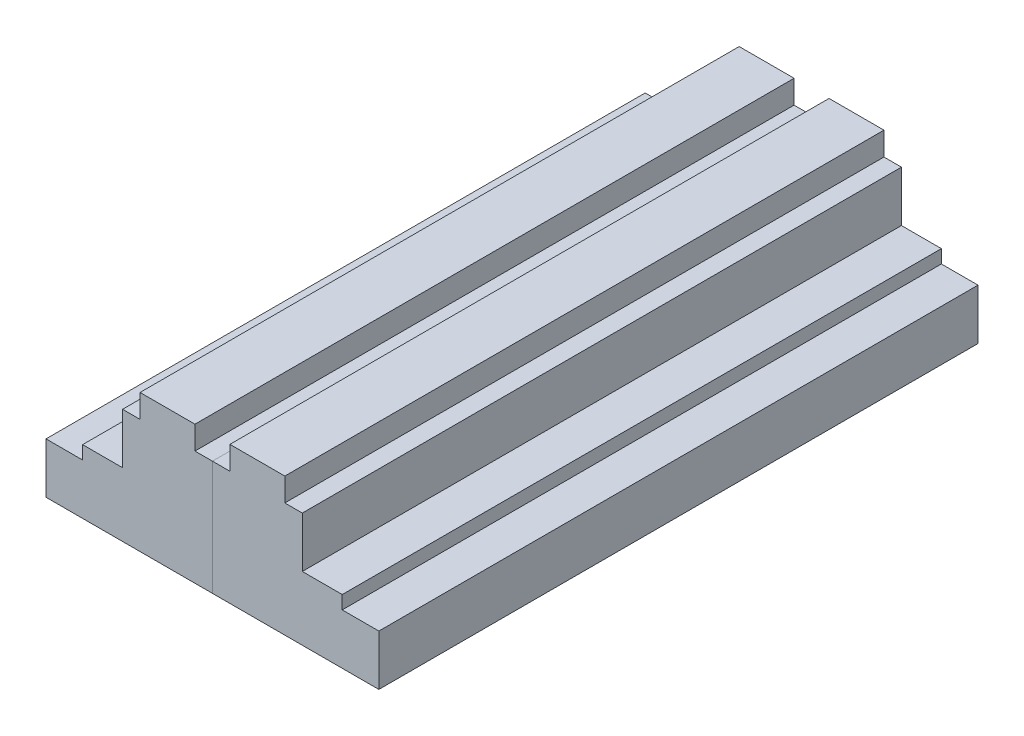
SolidWorks part; units mm, degrees
ref_plane "Front Plane" through (0, 0, 0) normal (0, 0, 1) x (1, 0, 0)
ref_plane "Top Plane" through (0, 0, 0) normal (0, 1, 0) x (1, 0, 0)
ref_plane "Right Plane" through (0, 0, 0) normal (1, 0, 0) x (0, 0, -1)
sketch "Sketch1" plane through (0, 0, 0) normal (0, 0, 1) x (1, 0, 0)
  line L0 (-25, 0) -> (-25, 7.6)
  line L1 (-25, 7.6) -> (-19.5, 7.6)
  line L2 (-19.5, 7.6) -> (-19.5, 9.6)
  line L3 (-19.5, 9.6) -> (-13.5, 9.6)
  line L4 (-13.5, 9.6) -> (-13.5, 17.2)
  line L5 (-13.5, 17.2) -> (-10.875, 17.2)
  line L6 (-10.875, 17.2) -> (-10.875, 20.7)
  line L7 (-10.875, 20.7) -> (-2.625, 20.7)
  line L8 (-2.625, 20.7) -> (-2.625, 17.2)
  line L9 (-2.625, 17.2) -> (0, 17.2)
  line L10 (0, 17.2) -> (0, 0)
  line L11 (-25, 0) -> (0, 0)
  point P2 (0, 0)
  point P14 (-26.7565, 13.1)
  point P15 (-16.5323, -7.6)
  point P16 (0, 0)
  point P17 (0, 0)
  point P18 (-38.3986, 13.1)
  point P19 (0, 0)
  point P20 (0, 0)
  point P21 (0, 0)
  point P22 (-23.0413, -7.6)
  point P23 (0, 16.6453)
  dimension "D1" = 8.25
  dimension "D2" = 25
  dimension "D3" = 19.5
  dimension "D4" = 13.5
  dimension "D5" = 20.7
  dimension "D6" = 2.625
  dimension "D7" = 7.6
  dimension "D8" = 2
  dimension "D9" = 7.6
  dimension "D10" = 3.5
extrude "Boss-Extrude1" add sketch "Sketch1" along normal blind 90 contours L11 L10 L9 L8 L7 L6 L5 L4 L3 L2 L1 L0
ref_plane "Plane1" through (10, 0, 0) normal (1, 0, 0) x (0, 0, -1)
mirror "Mirror1" about plane through (0, 17.2, 90) normal (1, 0, 0) of bodies 101
